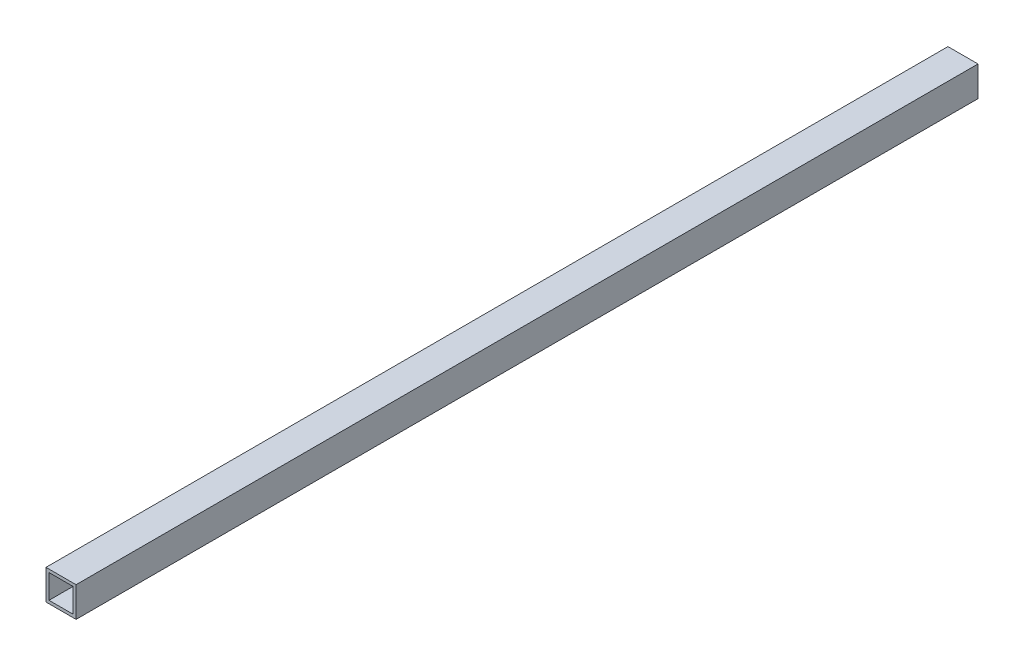
SolidWorks part; units mm, degrees
material "3.0205 (EN-AW 1200)"
ref_plane "前视基准面" through (0, 0, 0) normal (0, 0, 1) x (1, 0, 0)
ref_plane "上视基准面" through (0, 0, 0) normal (0, 1, 0) x (1, 0, 0)
ref_plane "右视基准面" through (0, 0, 0) normal (1, 0, 0) x (0, 0, -1)
sketch "草图1" plane through (0, 0, 0) normal (0, 0, 1) x (1, 0, 0)
  line L1 (-10, -10) -> (10, -10)
  line L2 (-10, -10) -> (-10, 10)
  line L3 (-10, 10) -> (10, 10)
  line L4 (10, -10) -> (10, 10)
  line L5 (-10, -10) -> (10, 10) construction
  line L6 (-10, 10) -> (10, -10) construction
  line L7 (-8, -8) -> (8, -8)
  line L8 (-8, -8) -> (-8, 8)
  line L9 (-8, 8) -> (8, 8)
  line L10 (8, -8) -> (8, 8)
  line L11 (-8, -8) -> (8, 8) construction
  line L12 (-8, 8) -> (8, -8) construction
  point P0 (0, 0)
  point P6 (0, 0)
  dimension "D1" = 16
  dimension "D2" = 20
  dimension "D3" = 20
extrude "凸台-拉伸1" add sketch "草图1" along normal blind 600
